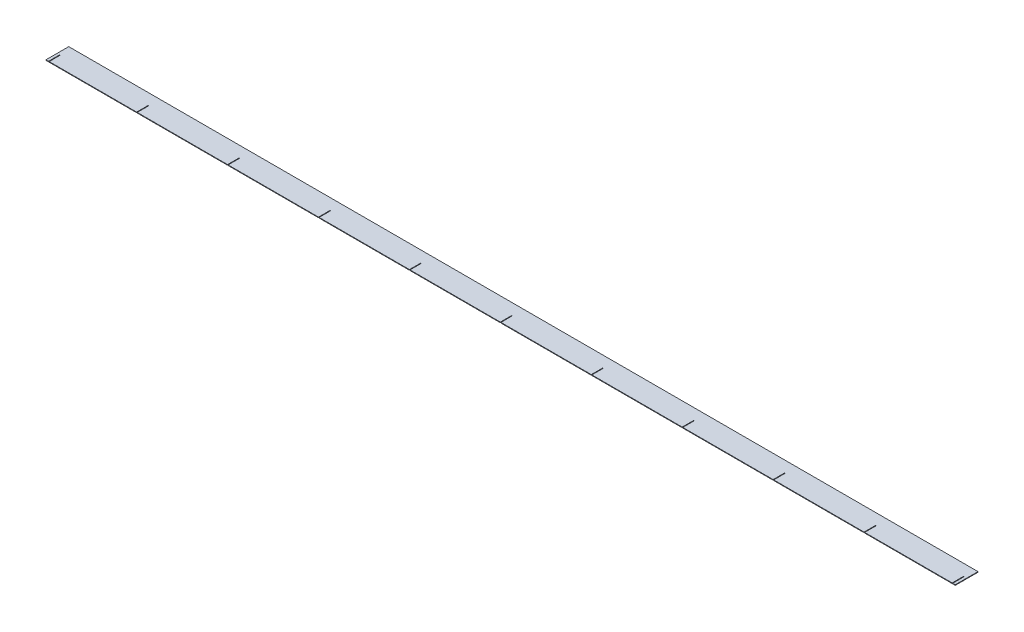
SolidWorks part; units mm, degrees
ref_plane "Front Plane" through (0, 0, 0) normal (0, 0, 1) x (1, 0, 0)
ref_plane "Top Plane" through (0, 0, 0) normal (0, 1, 0) x (1, 0, 0)
ref_plane "Right Plane" through (0, 0, 0) normal (1, 0, 0) x (0, 0, -1)
sketch "Sketch1" plane through (0, 0, 0) normal (0, 1, 0) x (1, 0, 0)
  line L0 (-800, 0) -> (800, 0) construction
  line L1 (-800, 20) -> (800, 20)
  line L2 (-800, 20) -> (-800, -20)
  line L3 (-800, -20) -> (800, -20) construction
  line L4 (800, 20) -> (800, -20)
  line L5 (-800, 20) -> (800, -20) construction
  line L6 (-800, -20) -> (800, 20) construction
  line L8 (-794.5, -20) -> (-794.5, 0)
  line L9 (-794.5, 0) -> (-795.5, 0)
  line L10 (-795.5, 0) -> (-795.5, -20)
  line L12 (-0.5, -20) -> (-0.5, 0)
  line L13 (-0.5, 0) -> (0.5, 0)
  line L14 (0.5, 0) -> (0.5, -20)
  line L16 (794.5, -20) -> (794.5, 0)
  line L17 (794.5, 0) -> (795.5, 0)
  line L18 (795.5, 0) -> (795.5, -20)
  line L19 (795.5, -20) -> (800, -20)
  line L20 (795, 0) -> (795, -20) construction
  line L21 (159.5, -20) -> (159.5, 0)
  line L22 (160, 0) -> (160, -20) construction
  line L23 (0, 0) -> (0, -20) construction
  line L24 (160.5, 0) -> (160.5, -20)
  line L25 (-795, 0) -> (-795, -20) construction
  line L26 (159.5, 0) -> (160.5, 0)
  line L27 (319.5, -20) -> (319.5, 0)
  line L28 (320, 0) -> (320, -20) construction
  line L29 (320.5, 0) -> (320.5, -20)
  line L30 (319.5, 0) -> (320.5, 0)
  line L31 (479.5, -20) -> (479.5, 0)
  line L32 (480, 0) -> (480, -20) construction
  line L33 (480.5, 0) -> (480.5, -20)
  line L34 (479.5, 0) -> (480.5, 0)
  line L35 (639.5, -20) -> (639.5, 0)
  line L36 (640, 0) -> (640, -20) construction
  line L37 (640.5, 0) -> (640.5, -20)
  line L38 (639.5, 0) -> (640.5, 0)
  line L39 (-160.5, -20) -> (-160.5, 0)
  line L40 (-160, 0) -> (-160, -20) construction
  line L41 (-159.5, 0) -> (-159.5, -20)
  line L42 (-160.5, 0) -> (-159.5, 0)
  line L43 (-320.5, -20) -> (-320.5, 0)
  line L44 (-320, 0) -> (-320, -20) construction
  line L45 (-319.5, 0) -> (-319.5, -20)
  line L46 (-320.5, 0) -> (-319.5, 0)
  line L47 (-480.5, -20) -> (-480.5, 0)
  line L48 (-480, 0) -> (-480, -20) construction
  line L49 (-479.5, 0) -> (-479.5, -20)
  line L50 (-480.5, 0) -> (-479.5, 0)
  line L51 (-640.5, -20) -> (-640.5, 0)
  line L52 (-640, 0) -> (-640, -20) construction
  line L53 (-639.5, 0) -> (-639.5, -20)
  line L54 (-640.5, 0) -> (-639.5, 0)
  line L55 (-159.5, -20) -> (-0.5, -20)
  line L56 (0.5, -20) -> (159.5, -20)
  line L57 (160.5, -20) -> (319.5, -20)
  line L58 (320.5, -20) -> (479.5, -20)
  line L59 (480.5, -20) -> (639.5, -20)
  line L60 (640.5, -20) -> (794.5, -20)
  line L61 (-160.5, -20) -> (-319.5, -20)
  line L62 (-320.5, -20) -> (-479.5, -20)
  line L63 (-480.5, -20) -> (-639.5, -20)
  line L64 (-640.5, -20) -> (-794.5, -20)
  line L65 (-800, -20) -> (-795.5, -20)
  point P0 (0, 0)
  dimension "D1" = 1600
  dimension "D2" = 40
  dimension "D3" = 5
  dimension "D4" = 1
  dimension "D5" = 5
  dimension "D6" = 1
  dimension "D7" = 5
  dimension "D8" = 1
  dimension "D10" = 160
  dimension "D11" = 160
  dimension "D9" = 5
extrude "Boss-Extrude1" add sketch "Sketch1" along normal blind 1
